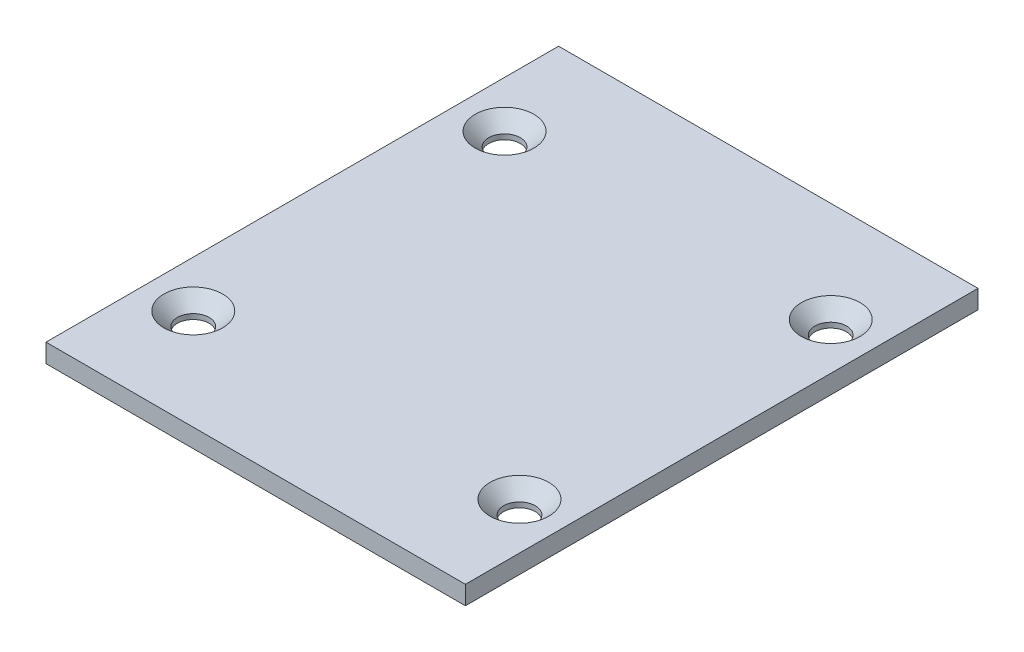
SolidWorks part; units mm, degrees
ref_plane "Front Plane" through (0, 0, 0) normal (0, 0, 1) x (1, 0, 0)
ref_plane "Top Plane" through (0, 0, 0) normal (0, 1, 0) x (1, 0, 0)
ref_plane "Right Plane" through (0, 0, 0) normal (1, 0, 0) x (0, 0, -1)
sketch "Sketch1" plane through (0, 0, 0) normal (0, 1, 0) x (1, 0, 0)
  line L0 (-17.5, -16.7) -> (17.5, -16.7) construction
  line L5 (-17.5, -16.7) -> (-17.5, 16.7) construction
  line L6 (-17.5, 16.7) -> (17.5, 16.7) construction
  line L7 (17.5, -16.7) -> (17.5, 16.7) construction
  line L8 (-17.5, -16.7) -> (17.5, 16.7) construction
  line L9 (-17.5, 16.7) -> (17.5, -16.7) construction
  line L10 (-31.0692, 0) -> (36.265, 0) construction
  line L11 (-20, 25) -> (20, 25) construction
  line L12 (-20, 25) -> (-20, -25) construction
  line L13 (-20, -25) -> (20, -25) construction
  line L14 (20, 25) -> (20, -25) construction
  line L15 (-22.5, -27.5) -> (22.5, -27.5)
  line L16 (-22.5, -27.5) -> (-22.5, 27.5)
  line L17 (-22.5, 27.5) -> (22.5, 27.5)
  line L18 (22.5, -27.5) -> (22.5, 27.5)
  line L19 (-2.5, -27.25) -> (2.5, -27.25)
  line L20 (-2.5, -27.25) -> (-2.5, -25.25)
  line L21 (-2.5, -25.25) -> (2.5, -25.25)
  line L22 (2.5, -27.25) -> (2.5, -25.25)
  line L23 (-2.5, 25.25) -> (2.5, 25.25)
  line L24 (2.5, 27.25) -> (2.5, 25.25)
  line L25 (-2.5, 27.25) -> (2.5, 27.25)
  line L26 (-2.5, 27.25) -> (-2.5, 25.25)
  point P0 (0, 16.7)
  point P9 (0, 25)
  point P15 (0, 27.5)
  point P16 (17.5, 0)
  point P17 (22.5, 0)
  point P18 (20, 0)
  point P24 (0, -27.25)
  dimension "D1" = 33.4
  dimension "D2" = 35
  dimension "D4" = 50
  dimension "D5" = 40
  dimension "D6" = 5
  dimension "D7" = 2.5
  dimension "D3" = 5
  dimension "D8" = 2
  dimension "D9" = 0.25
extrude "Boss-Extrude1" add sketch "Sketch1" along normal blind 2 contours L25 L26 L23 L24 | L15 L18 L17 L16 L26 L25 L24 L23 L22 L19 L20 L21 | L19 L22 L21 L20
hole_wizard "CSK for M3 Flat Head Machine Screw1" positions "Sketch4" profile "Sketch5" countersink size "M3" standard "ANSI Metric" end condition through all
sketch "Sketch4" plane through (0, 2, 0) normal (0, 1, 0) x (1, 0, 0)
  point P0 (-17.5, 16.7)
  point P3 (17.5, 16.7)
  point P6 (17.5, -16.7)
  point P9 (-17.5, -16.7)
sketch "Sketch5" plane through (-17.5, 2, -16.7) normal (1, 0, 0) x (0, 0, 1)
  line L0 (0, 0) -> (0, 2)
  line L1 (0, 2) -> (1.7, 2)
  line L2 (1.7, 2) -> (1.7, 1.45)
  line L3 (1.7, 1.45) -> (3.15, 0)
  line L5 (3.15, 0) -> (0, 0)
  line L6 (-1.7, 1.45) -> (-3.15, 0) construction
  line L11 (0, -6.35) -> (0, 107.95) construction
  dimension "Thru Hole Dia." = 3.4
  dimension "Thru Hole Depth" = 2
  dimension "Near C'Sink Dia." = 6.3
  dimension "Near C'Sink Angle" = 90
equation "\"D9@Sketch1\"=(\"D7@Sketch1\" - \"D8@Sketch1\")/2"
